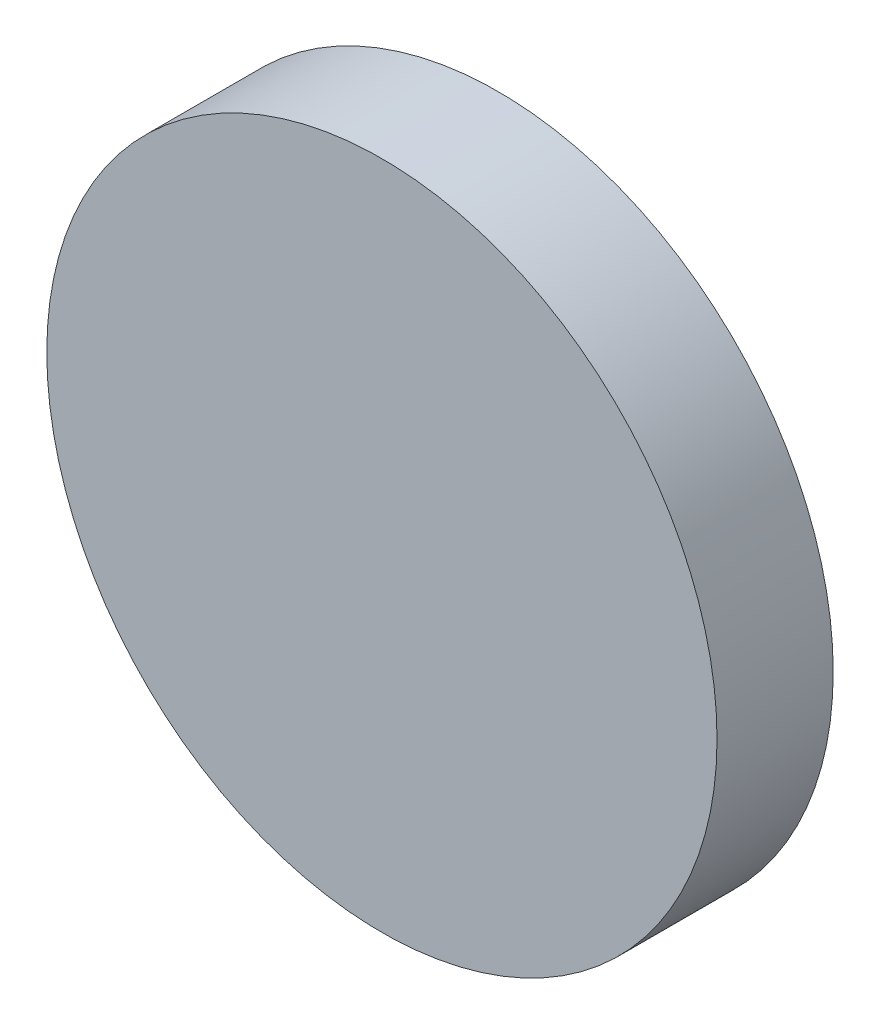
SolidWorks part; units mm, degrees
ref_plane "Front Plane" through (0, 0, 0) normal (0, 0, 1) x (1, 0, 0)
ref_plane "Top Plane" through (0, 0, 0) normal (0, 1, 0) x (1, 0, 0)
ref_plane "Right Plane" through (0, 0, 0) normal (1, 0, 0) x (0, 0, -1)
sketch "Sketch1" plane through (0, 0, 0) normal (0, 0, 1) x (1, 0, 0)
  circle A0 centre (0, 0) radius 47.625
  dimension "D1" = 95.25
extrude "Boss-Extrude1" add sketch "Sketch1" along normal blind 3.81
sketch "Sketch4" plane through (0, 0, 0) normal (0, 0, -1) x (-1, 0, 0)
  circle A0 centre (0, 0) radius 47.625
  circle A1 centre (0, 0) radius 44.45
  dimension "D1" = 88.9
extrude "Boss-Extrude2" add sketch "Sketch4" along normal blind 12.7
sketch "Sketch7" plane through (0, 0, 0) normal (0, 0, -1) x (-1, 0, 0)
  line L0 (-44.3842, -2.4176) -> (44.3842, -2.4176) construction
  line L1 (0, 44.45) -> (0, -43.7762) construction
  line L2 (-0.0792, -0.3493) -> (-0.0792, 44.1007) construction
  line L3 (-40.283, 5.5885) -> (40.1247, 5.5885) construction
  line L4 (-44.4782, 1.7785) -> (44.3199, 1.7785) construction
  line L5 (-40.283, 5.5885) -> (-44.4782, 1.7785) construction
  line L6 (40.1247, 5.5885) -> (44.3199, 1.7785) construction
  line L8 (-44.4546, -2.4176) -> (44.4454, -2.4176)
  line L9 (-44.4546, -2.4176) -> (-44.4546, -0.6396)
  line L10 (-44.4546, -0.6396) -> (44.4454, -0.6396)
  line L11 (44.4454, -2.4176) -> (44.4454, -0.6396)
  circle A0 centre (0, 0) radius 44.45 construction
  circle A1 centre (0, 0) radius 44.45 construction
  arc A2 (44.3199, 1.7785) -> (-44.4782, 1.7785) centre (-0.0792, -0.3493) ccw construction
  arc A3 (40.1247, 5.5885) -> (-40.283, 5.5885) centre (-0.0792, -0.3493) ccw construction
  dimension "D1" = 88.9
  dimension "D2" = 88.9
  dimension "D3" = 3.81
  dimension "D4" = 1.778
equation "\"D1@Boss-Extrude1\"=0.15"
